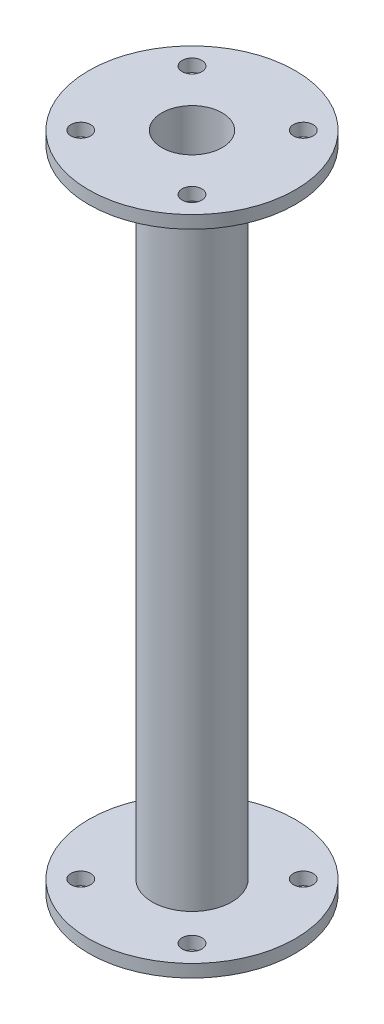
SolidWorks part; units mm, degrees
ref_plane "Front Plane" through (0, 0, 0) normal (0, 0, 1) x (1, 0, 0)
ref_plane "Top Plane" through (0, 0, 0) normal (0, 1, 0) x (1, 0, 0)
ref_plane "Right Plane" through (0, 0, 0) normal (1, 0, 0) x (0, 0, -1)
sketch "Sketch1" plane through (0, 0, 0) normal (0, 1, 0) x (1, 0, 0)
  line L1 (17.5, 17.5) -> (-17.5, 17.5) construction
  line L2 (17.5, 17.5) -> (17.5, -17.5) construction
  line L3 (17.5, -17.5) -> (-17.5, -17.5) construction
  line L4 (-17.5, 17.5) -> (-17.5, -17.5) construction
  line L5 (17.5, 17.5) -> (-17.5, -17.5) construction
  line L6 (17.5, -17.5) -> (-17.5, 17.5) construction
  circle A0 centre (0, 0) radius 9.5
  circle A1 centre (0, 0) radius 32.5
  circle A2 centre (-17.5, 17.5) radius 3.1
  circle A3 centre (17.5, 17.5) radius 3.1
  circle A4 centre (17.5, -17.5) radius 3.1
  circle A5 centre (-17.5, -17.5) radius 3.1
  point P4 (0, 0)
  dimension "D1" = 19
  dimension "D3" = 65
  dimension "D4" = 6.2
  dimension "D2" = 35
extrude "Boss-Extrude1" add sketch "Sketch1" along normal blind 4
sketch "Sketch2" plane through (0, 4, 0) normal (0, 1, 0) x (1, 0, 0)
  circle A0 centre (0, 0) radius 9.5 construction
  circle A1 centre (0, 0) radius 9.5
  circle A2 centre (0, 0) radius 12.5
  dimension "D1" = 25
  dimension "D2" = 3
extrude "Boss-Extrude2" add sketch "Sketch2" along normal blind 200
sketch "Sketch3" plane through (0, 204, 0) normal (0, 1, 0) x (1, 0, 0)
  circle A0 centre (0, 0) radius 32.5 construction
  circle A1 centre (-17.5, 17.5) radius 3.1 construction
  circle A2 centre (17.5, 17.5) radius 3.1 construction
  circle A3 centre (17.5, -17.5) radius 3.1 construction
  circle A4 centre (-17.5, -17.5) radius 3.1 construction
  circle A5 centre (0, 0) radius 9.5 construction
  circle A6 centre (0, 0) radius 32.5
  circle A7 centre (-17.5, 17.5) radius 3.1
  circle A8 centre (17.5, 17.5) radius 3.1
  circle A9 centre (17.5, -17.5) radius 3.1
  circle A10 centre (-17.5, -17.5) radius 3.1
  circle A11 centre (0, 0) radius 9.5
extrude "Boss-Extrude3" add sketch "Sketch3" along normal blind 4
